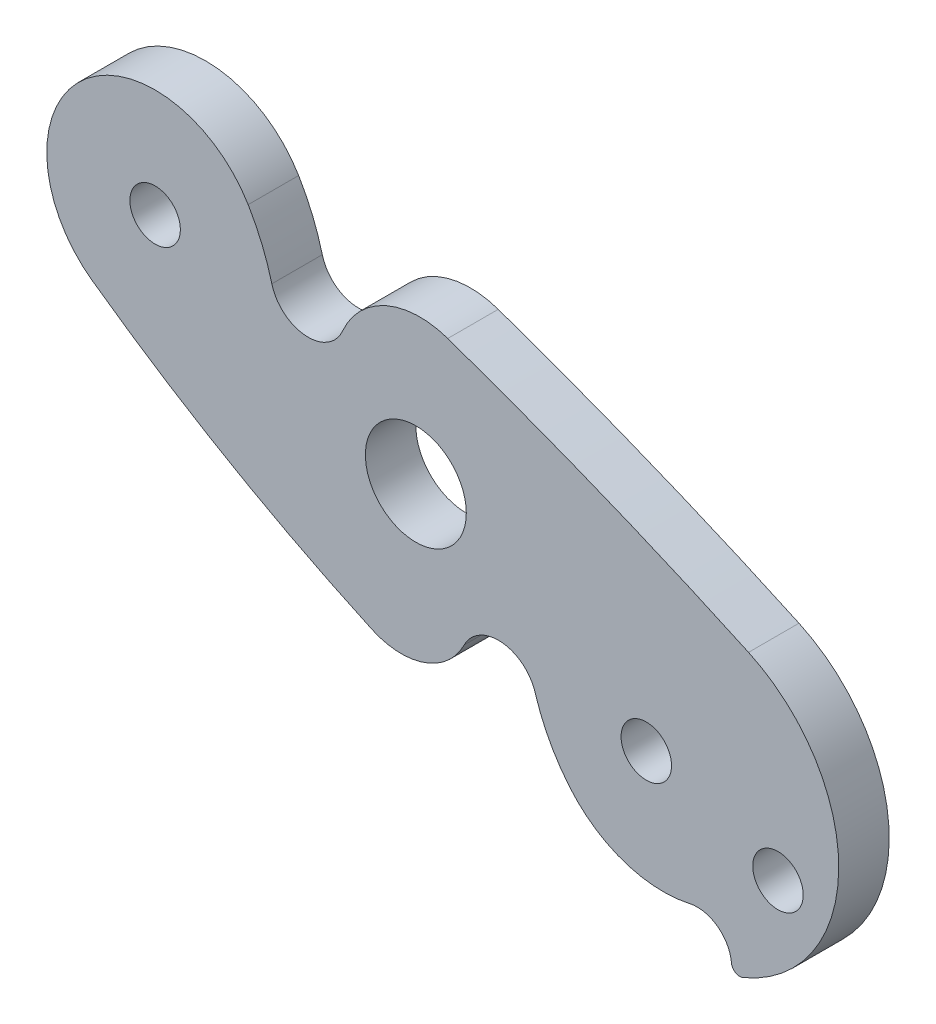
SolidWorks part; units mm, degrees
ref_plane "Plan de face" through (0, 0, 0) normal (0, 0, 1) x (1, 0, 0)
ref_plane "Plan de dessus" through (0, 0, 0) normal (0, 1, 0) x (1, 0, 0)
ref_plane "Plan de droite" through (0, 0, 0) normal (1, 0, 0) x (0, 0, -1)
sketch "Esquisse1" plane through (0, 0, 0) normal (0, 0, 1) x (1, 0, 0)
  line L0 (67.3315, 456.2081) -> (148.7221, 398.1085) construction
  line L1 (-15.5, 6.1) -> (-6.4028, 6.5835) construction
  circle A0 centre (0, 0) radius 3
  circle A1 centre (-15.5, 6.1) radius 1.5
  circle A2 centre (13.7, -6.9) radius 1.5
  arc A4 (-9.968, 9.3984) -> (-19.2559, 0.8678) centre (-15.5, 6.1) ccw
  arc A5 (-9.968, 9.3984) -> (-8.5611, 6.026) centre (-21.0236, 2.8067) cw
  arc A6 (-8.5611, 6.026) -> (-4.3573, 5.6976) centre (-6.4028, 6.5835) ccw
  arc A7 (-4.3573, 5.6976) -> (1.8991, 8.4431) centre (0.2487, 3.7026) cw
  arc A8 (1.8991, 8.4431) -> (19.779, 1.222) centre (-63.0619, -178.1511) cw
  arc A9 (19.779, 1.222) -> (18.7075, -15.9594) centre (15.9076, -7.1607) cw
  arc A10 (18.7075, -15.9594) -> (16.2867, -13.4637) centre (16.7317, -15.454) ccw
  arc A11 (16.2867, -13.4637) -> (9.1069, -10.9843) centre (14.7076, -6.4013) cw
  arc A12 (9.1069, -10.9843) -> (7.101, -7.2145) centre (17.5578, -4.0691) cw
  arc A13 (7.101, -7.2145) -> (2.8696, -6.8566) centre (4.9145, -7.8722) ccw
  arc A14 (2.8696, -6.8566) -> (-2.5991, -8.7946) centre (-0.8655, -5.0016) cw
  arc A15 (-2.5991, -8.7946) -> (-19.2559, 0.8678) centre (38.7508, 81.6763) cw
  circle A16 centre (21.53, -9.6534) radius 1.5
  dimension "D2" = 6
  dimension "D7" = 3
  dimension "D9" = 3
  dimension "D1" = 100
  dimension "D3" = 15.5
  dimension "D4" = 6.1
  dimension "D5" = 13.7
  dimension "D6" = 6.9
  dimension "D8" = 9.11
  dimension "D10" = 8.3
  dimension "D11" = 7.83
extrude "Boss.-Extru.1" add sketch "Esquisse1" along normal blind 3
fillet "Congé1" radius 0.5 1 edges at (18.7075, -15.9594, 1.5)
